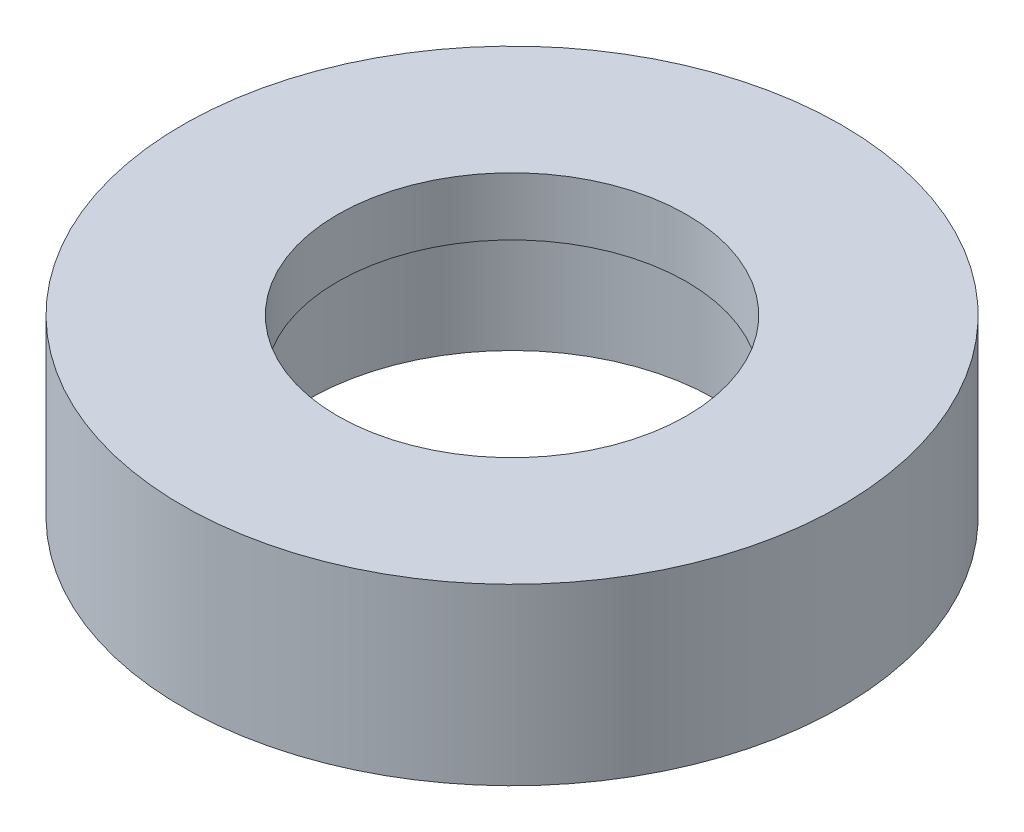
SolidWorks part; units mm, degrees
ref_plane "Alzado" through (0, 0, 0) normal (0, 0, 1) x (1, 0, 0)
ref_plane "Planta" through (0, 0, 0) normal (0, 1, 0) x (1, 0, 0)
ref_plane "Vista lateral" through (0, 0, 0) normal (1, 0, 0) x (0, 0, -1)
sketch "Croquis3" plane through (0, 0, 0) normal (0, 0, 1) x (1, 0, 0)
  line L0 (0, 0) -> (0, 22.7851) construction
  line L1 (-18, 17.5006) -> (-34, 17.5006)
  line L2 (-34, 17.5006) -> (-34, -0.4994)
  line L3 (-34, -0.4994) -> (-21, -0.4994)
  line L4 (-21, -0.4994) -> (-21, 11.5006)
  line L5 (-21, 11.5006) -> (-18, 11.5006)
  line L6 (-18, 11.5006) -> (-18, 17.5006)
  dimension "D1" = 34
  dimension "D2" = 12
  dimension "D3" = 6
  dimension "D4" = 21
  dimension "D5" = 18
revolve "Revolución1" add sketch "Croquis3" angle 360 about L0
sketch "Croquis4" plane through (0, -0.4994, 0) normal (0, -1, 0) x (1, 0, 0)
  line L0 (0, 0) -> (0, 27.6) construction
  line L1 (0, 0) -> (27.6, 0) construction
  line L2 (0, 0) -> (0, -27.6) construction
  line L3 (0, 0) -> (-27.6, 0) construction
  circle A0 centre (0, 27.6) radius 3
  circle A1 centre (27.6, 0) radius 3
  circle A2 centre (0, -27.6) radius 3
  circle A3 centre (-27.6, 0) radius 3
  point P7 (0, 0)
  dimension "D4" = 6
  dimension "D5" = 6
  dimension "D6" = 6
  dimension "D7" = 6
  dimension "D1" = 27.6
  dimension "D2" = 27.6
  dimension "D3" = 27.6
extrude "Cortar-Extruir2" cut sketch "Croquis4" against normal blind 10
